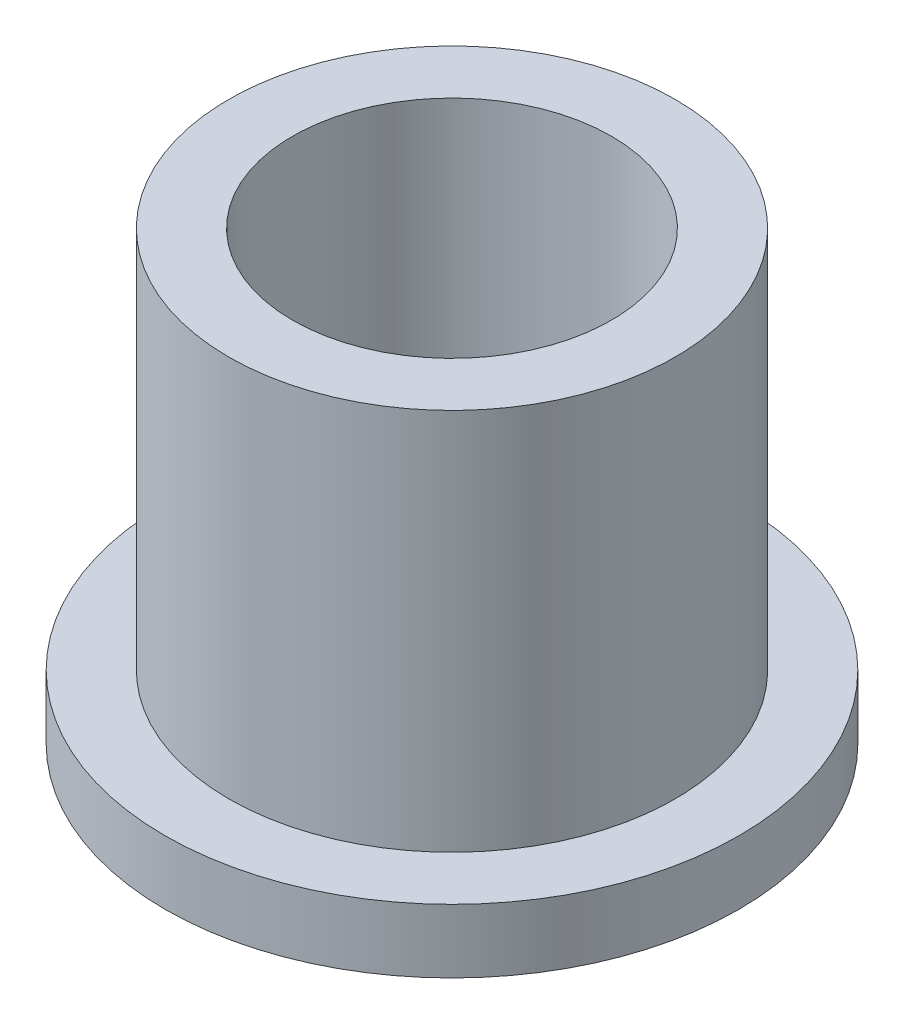
SolidWorks part; units mm, degrees
ref_plane "Front" through (0, 0, 0) normal (0, 0, 1) x (1, 0, 0)
ref_plane "Top" through (0, 0, 0) normal (0, 1, 0) x (1, 0, 0)
ref_plane "Right" through (0, 0, 0) normal (1, 0, 0) x (0, 0, -1)
sketch "Sketch1" plane through (0, 0, 0) normal (0, 1, 0) x (1, 0, 0)
  circle A0 centre (0, 0) radius 3.9688
  circle A1 centre (0, 0) radius 5.5562
  circle A2 centre (0, 0) radius 7.1438
  dimension "ID" = 7.9375
  dimension "OD" = 11.1125
  dimension "FlangeOD" = 14.2875
sketch "Sketch2" plane through (0, 0, 0) normal (0, 1, 0) x (1, 0, 0)
  circle A0 centre (0, 0) radius 3.9688 construction
  circle A1 centre (0, 0) radius 5.5562 construction
  circle A2 centre (0, 0) radius 3.9688
  circle A3 centre (0, 0) radius 5.5562
extrude "Boss-Extrude1" add sketch "Sketch2" along normal blind 11.1125
sketch "Sketch3" plane through (0, 0, 0) normal (0, 1, 0) x (1, 0, 0)
  circle A0 centre (0, 0) radius 7.1438 construction
  circle A1 centre (0, 0) radius 5.5562 construction
  circle A2 centre (0, 0) radius 7.1438
  circle A3 centre (0, 0) radius 5.5562
extrude "Boss-Extrude2" add sketch "Sketch3" along normal blind 1.5875
